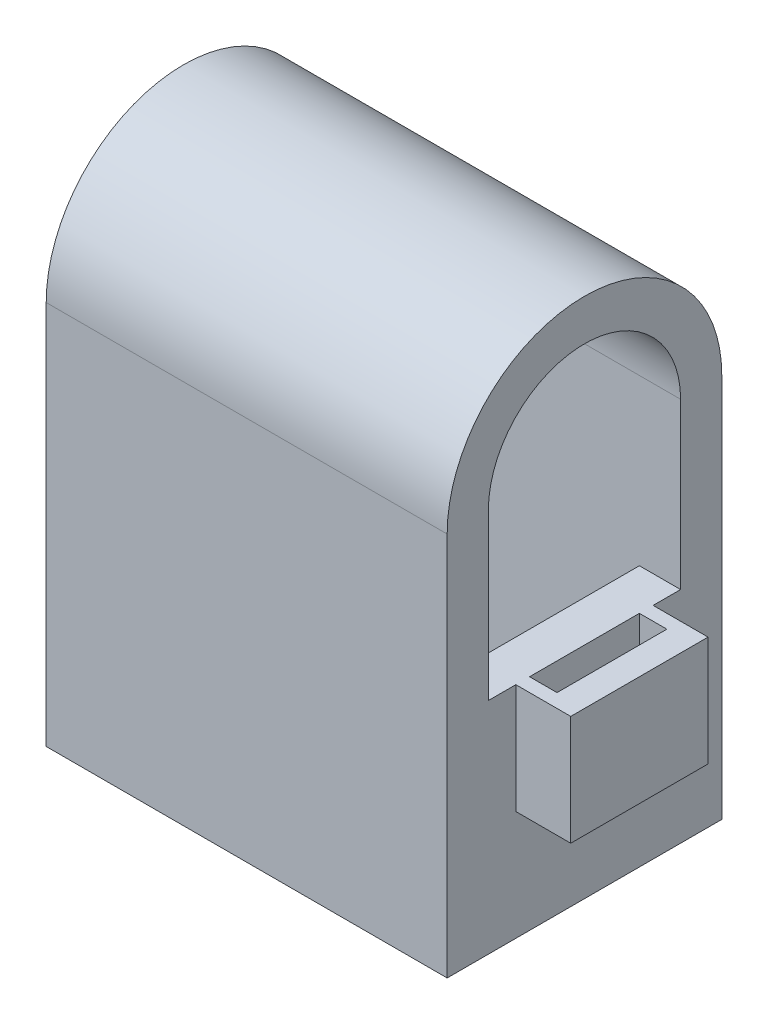
SolidWorks part; units mm, degrees
ref_plane "Front Plane" through (0, 0, 0) normal (0, 0, 1) x (1, 0, 0)
ref_plane "Top Plane" through (0, 0, 0) normal (0, 1, 0) x (1, 0, 0)
ref_plane "Right Plane" through (0, 0, 0) normal (1, 0, 0) x (0, 0, -1)
sketch "Sketch1" plane through (0, 0, 0) normal (0, 0, 1) x (1, 0, 0)
  line L1 (-9.271, -8.89) -> (9.271, -8.89)
  line L2 (-9.271, -8.89) -> (-9.271, 8.89)
  line L3 (-9.271, 8.89) -> (9.271, 8.89)
  line L4 (9.271, -8.89) -> (9.271, 8.89)
  line L5 (-9.271, -8.89) -> (9.271, 8.89) construction
  line L6 (-9.271, 8.89) -> (9.271, -8.89) construction
  point P0 (0, 0)
  dimension "D1" = 17.78
  dimension "D2" = 18.542
ref_plane "Plane2" through (0, 0, -12.7) normal (0, 0, 1) x (1, 0, 0)
sketch "Sketch4" plane through (0, 0, -12.7) normal (0, 0, 1) x (1, 0, 0)
  line L1 (9.271, -8.89) -> (-9.271, -8.89)
  line L2 (9.271, -8.89) -> (9.271, 8.89)
  line L3 (9.271, 8.89) -> (-9.271, 8.89)
  line L4 (-9.271, -8.89) -> (-9.271, 8.89)
  line L5 (9.271, -8.89) -> (-9.271, 8.89) construction
  line L6 (9.271, 8.89) -> (-9.271, -8.89) construction
  point P0 (0, 0)
extrude "Boss-Extrude4" add sketch "Sketch1" against normal blind 1.905
extrude "Boss-Extrude5" add sketch "Sketch4" along normal blind 1.905 separate body
ref_plane "Plane3" through (0, 0, -6.35) normal (0, 0, 1) x (1, 0, 0)
ref_plane "Plane4" through (0, 8.89, 0) normal (0, 1, 0) x (1, 0, 0)
ref_plane "Plane5" through (-9.271, 0, 0) normal (-1, 0, 0) x (0, 0, 1)
sketch "Sketch6" plane through (-9.271, 0, 0) normal (-1, 0, 0) x (0, 0, 1)
  line L0 (-12.7, 0) -> (0, 0) construction
  line L1 (-12.7, -5.4994) -> (-12.7, 5.4994) construction
  line L2 (-1.905, 8.89) -> (-1.905, -8.89) construction
  line L3 (10.1981, 8.89) -> (-10.1981, 8.89) construction
  line L4 (-6.35, 8.89) -> (-6.35, 7.62) construction
  line L5 (-10.795, 8.89) -> (-12.7, 8.89) construction
  line L6 (-12.7, 8.89) -> (-10.795, 8.89)
  line L7 (-1.905, 8.89) -> (0, 8.89)
  arc A0 (-10.795, 8.89) -> (-1.905, 8.89) centre (-6.35, 8.89) cw
  arc A1 (0, 8.89) -> (-12.7, 8.89) centre (-6.35, 8.89) ccw
extrude "Boss-Extrude6" add sketch "Sketch6" against normal up to surface (18.542 mm away) up to face at (9.271, 0, -0.9525)
sketch "Sketch7" plane through (-9.271, 0, 0) normal (-1, 0, 0) x (0, 0, 1)
  line L0 (-1.905, 8.89) -> (-1.905, -8.89) construction
  line L1 (-10.795, -8.89) -> (-1.905, -8.89)
  line L2 (-10.795, -8.89) -> (-10.795, 1.27)
  line L3 (-10.795, 1.27) -> (-1.905, 1.27)
  line L4 (-1.905, -8.89) -> (-1.905, 1.27)
  dimension "D1" = 10.16
extrude "Boss-Extrude7" add sketch "Sketch7" against normal blind 1.905
ref_plane "Plane8" through (0, 0, 0) normal (-1, 0, 0) x (0, 0, 1)
ref_plane "Plane9" through (9.271, 0, 0) normal (1, 0, 0) x (0, 0, -1)
sketch "Sketch8" plane through (9.271, 0, 0) normal (1, 0, 0) x (0, 0, -1)
  line L5 (1.905, -8.89) -> (10.795, -8.89)
  line L6 (1.905, -8.89) -> (1.905, 1.27)
  line L7 (1.905, 1.27) -> (10.795, 1.27)
  line L8 (10.795, -8.89) -> (10.795, 1.27)
extrude "Boss-Extrude8" add sketch "Sketch8" against normal blind 1.905
sketch "Sketch9" plane through (9.271, 0, 0) normal (1, 0, 0) x (0, 0, -1)
  line L0 (6.35, 1.27) -> (6.35, -8.89) construction
  line L1 (10.795, 1.27) -> (1.905, 1.27) construction
  line L2 (12.7, -8.89) -> (0, -8.89) construction
  line L3 (9.525, -3.81) -> (3.175, -3.81) construction
  line L5 (3.175, -3.81) -> (9.525, -3.81)
  line L6 (3.175, -3.81) -> (3.175, 1.27)
  line L7 (3.175, 1.27) -> (9.525, 1.27)
  line L8 (9.525, -3.81) -> (9.525, 1.27)
  point P9 (6.35, -3.81)
extrude "Boss-Extrude9" add sketch "Sketch9" along normal blind 2.54
sketch "Sketch10" plane through (0, 1.27, 0) normal (0, 1, 0) x (1, 0, 0)
  line L0 (10.541, 9.525) -> (10.541, 3.175) construction
  line L1 (11.811, 9.525) -> (9.271, 9.525) construction
  line L2 (11.811, 3.175) -> (9.271, 3.175) construction
  line L3 (10.541, 6.35) -> (11.811, 6.35) construction
  line L4 (11.811, 9.525) -> (11.811, 3.175) construction
  line L5 (9.271, 8.89) -> (9.271, 3.81) construction
  line L6 (9.271, -6.985) -> (9.271, 6.985) construction
  line L7 (10.541, 6.35) -> (9.271, 6.35) construction
  line L8 (9.271, 8.89) -> (9.271, 3.81)
  line L9 (9.271, 3.81) -> (10.541, 3.81)
  line L10 (10.541, 3.81) -> (10.541, 8.89)
  line L11 (10.541, 8.89) -> (9.271, 8.89)
extrude "Cut-Extrude1" cut sketch "Sketch10" against normal through all
